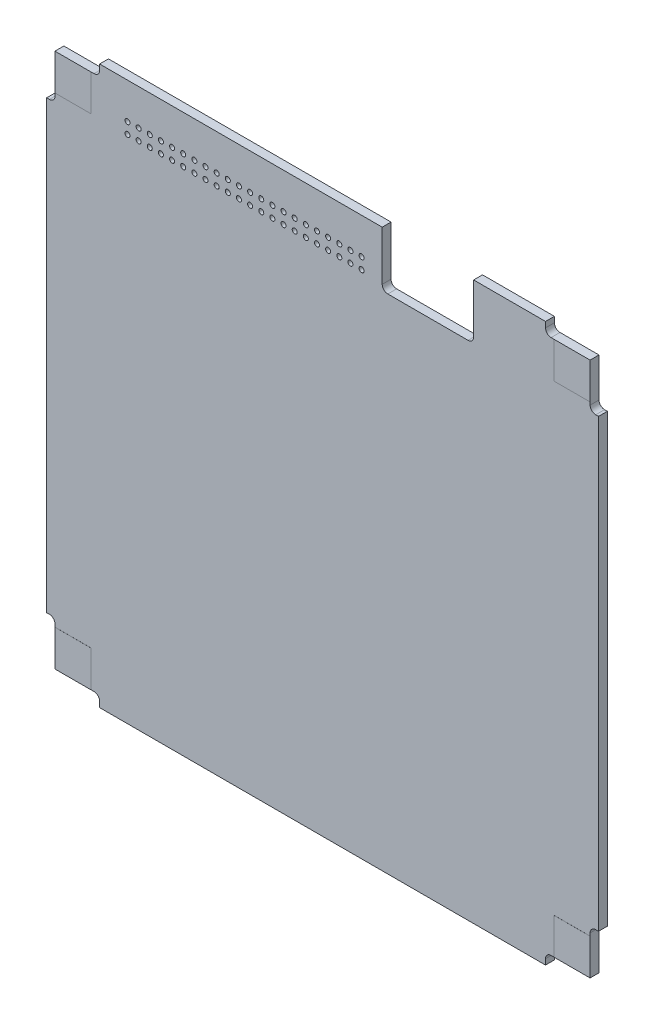
SolidWorks part; units mm, degrees
material "ABS"
ref_plane "Front Plane" through (0, 0, 0) normal (0, 0, 1) x (1, 0, 0)
ref_plane "Top Plane" through (0, 0, 0) normal (0, 1, 0) x (1, 0, 0)
ref_plane "Right Plane" through (0, 0, 0) normal (1, 0, 0) x (0, 0, -1)
sketch "Sketch1" plane through (0, 0, 0) normal (0, 0, 1) x (1, 0, 0)
  line L0 (-40, 50) -> (-40, 48)
  line L1 (-50, -50) -> (50, -50)
  line L2 (-50, -50) -> (-50, 50)
  line L3 (-50, 50) -> (50, 50)
  line L4 (50, -50) -> (50, 50)
  line L5 (-50, -50) -> (50, 50) construction
  line L6 (-50, 50) -> (50, -50) construction
  line L7 (-50, 50) -> (-40, 50)
  line L8 (-50, 50) -> (-50, 40)
  line L9 (-40, 48) -> (-48, 48)
  line L10 (-48, 48) -> (-48, 40)
  line L11 (50, 50) -> (40, 50)
  line L12 (50, 50) -> (50, 40)
  line L13 (-48, 40) -> (-50, 40)
  line L14 (50, 40) -> (48, 40)
  line L15 (-50, -50) -> (-37.8649, -50)
  line L16 (-50, -50) -> (-50, -37.8649)
  line L17 (50, 50) -> (50, 40)
  line L18 (50, 50) -> (40, 50)
  line L19 (50, -50) -> (41.5, -50)
  line L20 (50, -50) -> (50, -41.5)
  line L21 (48, 40) -> (48, 48)
  line L22 (48, 48) -> (40, 48)
  line L23 (40, 48) -> (40, 50)
  line L24 (40, -50) -> (40, -48)
  line L25 (50, -50) -> (40, -50)
  line L26 (50, -50) -> (50, -40)
  line L27 (40, -48) -> (48, -48)
  line L28 (48, -48) -> (48, -40)
  line L29 (48, -40) -> (50, -40)
  line L30 (-50, -40) -> (-48, -40)
  line L31 (-50, -50) -> (-50, -40)
  line L32 (-50, -50) -> (-40, -50)
  line L33 (-48, -40) -> (-48, -48)
  line L34 (-48, -48) -> (-40, -48)
  line L35 (-40, -48) -> (-40, -50)
  point P0 (0, 0)
  point P38 (0, 0)
  dimension "D1" = 100
  dimension "D2" = 100
  dimension "D3" = 2
  dimension "D4" = 10
  dimension "D5" = 4
extrude "Boss-Extrude1" add sketch "Sketch1" along normal blind 1.5875
fillet "Fillet1" radius 1 8 edges at (-48, -40, 0.7937) (-40, -48, 0.7937) (40, -48, 0.7937) (48, -40, 0.7937) (48, 40, 0.7937) (40, 48, 0.7937) (-40, 48, 0.7937) (-48, 40, 0.7937)
sketch "Sketch2" plane through (0, 0, 1.5875) normal (0, 0, 1) x (1, 0, 0)
  line L0 (0, 50) -> (0, -50) construction
  line L1 (-40, 50) -> (40, 50) construction
  line L2 (-40, -50) -> (40, -50) construction
  line L4 (-36, 45.8) -> (8, 45.8) construction
  line L5 (-36, 45.8) -> (-36, 43.55) construction
  line L6 (-36, 43.55) -> (8, 43.55) construction
  line L7 (8, 45.8) -> (8, 43.55) construction
  line L8 (-36, 50) -> (8, 50) construction
  line L9 (-36, 50) -> (-36, 45.8) construction
  line L10 (-36, 45.8) -> (8, 45.8) construction
  line L11 (8, 50) -> (8, 45.8) construction
  circle A0 centre (-35, 43.55) radius 0.45
  circle A1 centre (-33, 43.55) radius 0.45
  circle A2 centre (-31, 43.55) radius 0.45
  circle A3 centre (-29, 43.55) radius 0.45
  circle A4 centre (-27, 43.55) radius 0.45
  circle A5 centre (-25, 43.55) radius 0.45
  circle A6 centre (-23, 43.55) radius 0.45
  circle A7 centre (-21, 43.55) radius 0.45
  circle A8 centre (-19, 43.55) radius 0.45
  circle A9 centre (-17, 43.55) radius 0.45
  circle A10 centre (-15, 43.55) radius 0.45
  circle A11 centre (-13, 43.55) radius 0.45
  circle A12 centre (-11, 43.55) radius 0.45
  circle A13 centre (-9, 43.55) radius 0.45
  circle A14 centre (-7, 43.55) radius 0.45
  circle A15 centre (-5, 43.55) radius 0.45
  circle A16 centre (-3, 43.55) radius 0.45
  circle A17 centre (-1, 43.55) radius 0.45
  circle A18 centre (1, 43.55) radius 0.45
  circle A19 centre (3, 43.55) radius 0.45
  circle A20 centre (5, 43.55) radius 0.45
  circle A21 centre (7, 43.55) radius 0.45
  circle A22 centre (-33, 41.55) radius 0.45
  circle A23 centre (-31, 41.55) radius 0.45
  circle A24 centre (-29, 41.55) radius 0.45
  circle A25 centre (-27, 41.55) radius 0.45
  circle A26 centre (-25, 41.55) radius 0.45
  circle A27 centre (-23, 41.55) radius 0.45
  circle A28 centre (-21, 41.55) radius 0.45
  circle A29 centre (-19, 41.55) radius 0.45
  circle A30 centre (-17, 41.55) radius 0.45
  circle A31 centre (-15, 41.55) radius 0.45
  circle A32 centre (-13, 41.55) radius 0.45
  circle A33 centre (-11, 41.55) radius 0.45
  circle A34 centre (-9, 41.55) radius 0.45
  circle A35 centre (-7, 41.55) radius 0.45
  circle A36 centre (-5, 41.55) radius 0.45
  circle A37 centre (-3, 41.55) radius 0.45
  circle A38 centre (-1, 41.55) radius 0.45
  circle A39 centre (1, 41.55) radius 0.45
  circle A40 centre (3, 41.55) radius 0.45
  circle A41 centre (5, 41.55) radius 0.45
  circle A42 centre (7, 41.55) radius 0.45
  circle A43 centre (-35, 41.55) radius 0.45
  dimension "D1" = 0.9
  dimension "D6" = 15
  dimension "D4" = 42
  dimension "D5" = 2
  dimension "D7" = 2.25
  dimension "D8" = 44
  dimension "D10" = 1
  dimension "D11" = 4.2
  dimension "D2" = 22
  dimension "D3" = 2
extrude "Cut-Extrude1" cut sketch "Sketch2" against normal through all
sketch "Sketch3" plane through (0, 50, 0) normal (0, 1, 0) x (1, 0, 0)
  line L0 (-40, 0) -> (40, 0) construction
  line L1 (10.7, 0) -> (19.7, 0)
  line L2 (10.7, 0) -> (10.7, -1.5875)
  line L3 (10.7, -1.5875) -> (19.7, -1.5875)
  line L5 (-40, -1.5875) -> (40, -1.5875) construction
  line L6 (15.2, 0) -> (15.2, -1.5875) construction
  line L7 (12, 0) -> (12, -1.5875) construction
  line L8 (18.4, 0) -> (18.4, -1.5875) construction
  line L9 (-40, -1.5875) -> (40, -1.5875) construction
  line L10 (7, 0) -> (7, -1.5875) construction
  line L11 (6.55, -1.5875) -> (7.45, -1.5875) construction
  line L12 (19.7, 0) -> (27.1, 0)
  line L14 (19.7, -1.5875) -> (27.1, -1.5875)
  line L15 (27.1, 0) -> (27.1, -1.5875)
  dimension "D1" = 9
  dimension "D2" = 6.4
  dimension "D3" = 3.2
  dimension "D4" = 5
  dimension "D5" = 7.4
extrude "Cut-Extrude2" cut sketch "Sketch3" against normal blind 9.8806
fillet "Fillet2" radius 1 2 edges at (10.7, 40.1194, 0.7938) (27.1, 40.1194, 0.7937)
sketch "Sketch4" plane through (0, 0, 1.5875) normal (0, 0, 1) x (1, 0, 0)
  line L1 (-48, 48) -> (-41.5, 48)
  line L2 (-48, 48) -> (-48, 41.5)
  line L3 (-48, 41.5) -> (-41.5, 41.5)
  line L4 (-41.5, 48) -> (-41.5, 41.5)
  line L5 (-48, -48) -> (-41.5, -48)
  line L6 (-48, -48) -> (-48, -41.5)
  line L7 (-48, -41.5) -> (-41.5, -41.5)
  line L8 (-41.5, -48) -> (-41.5, -41.5)
  line L9 (48, -48) -> (41.5, -48)
  line L10 (48, -48) -> (48, -41.5)
  line L11 (48, -41.5) -> (41.5, -41.5)
  line L12 (41.5, -48) -> (41.5, -41.5)
  line L13 (48, 48) -> (41.5, 48)
  line L14 (48, 48) -> (48, 41.5)
  line L15 (48, 41.5) -> (41.5, 41.5)
  line L16 (41.5, 48) -> (41.5, 41.5)
  dimension "D1" = 6.5
extrude "Boss-Extrude2" add sketch "Sketch4" along normal blind 0.01
sketch "Sketch5" plane through (0, 0, 0) normal (0, 0, -1) x (-1, 0, 0)
  line L0 (40, -50) -> (-40, -50) construction
  line L1 (-49.5, 50) -> (49.5, 50)
  line L2 (-49.5, 50) -> (-49.5, -50)
  line L3 (-49.5, -50) -> (49.5, -50)
  line L4 (49.5, 50) -> (49.5, -50)
  line L5 (40, 50) -> (-10.7, 50) construction
  line L6 (50, -40) -> (50, 40) construction
  dimension "D1" = 99
  dimension "D2" = 0.5
extrude "Cut-Extrude3" cut sketch "Sketch5" against normal through all flip side to cut
